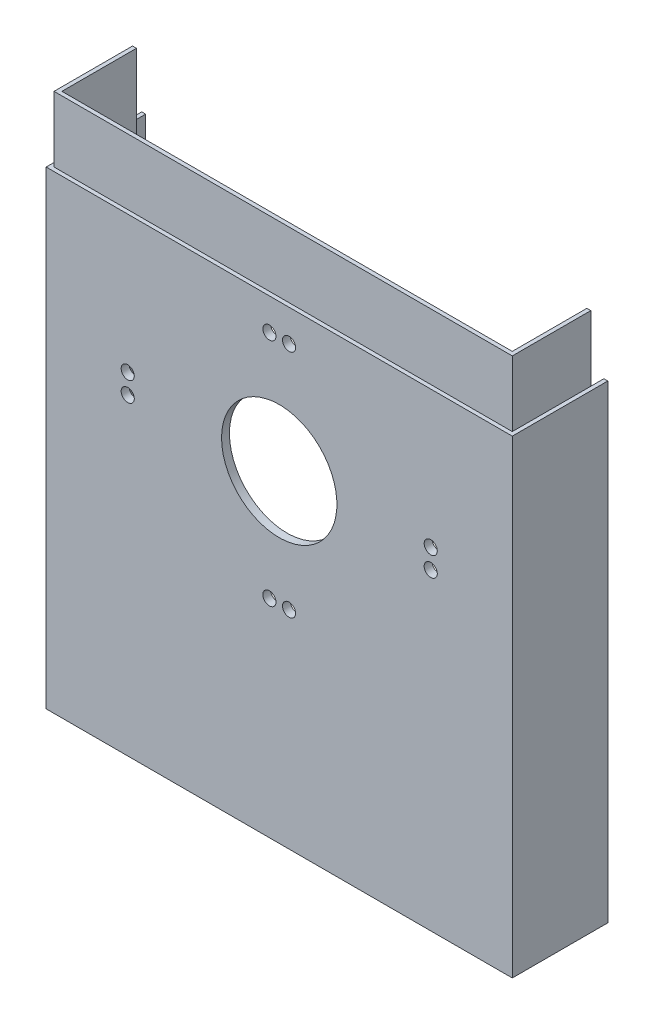
SolidWorks part; units mm, degrees
ref_plane "Front Plane" through (0, 0, 0) normal (0, 0, 1) x (1, 0, 0)
ref_plane "Top Plane" through (0, 0, 0) normal (0, 1, 0) x (1, 0, 0)
ref_plane "Right Plane" through (0, 0, 0) normal (1, 0, 0) x (0, 0, -1)
sketch "Sketch1" plane through (0, 0, 0) normal (0, 0, 1) x (1, 0, 0)
  line L1 (-88.9, -127) -> (88.9, -127)
  line L2 (-88.9, -127) -> (-88.9, 127)
  line L3 (-88.9, 127) -> (88.9, 127)
  line L4 (88.9, -127) -> (88.9, 127)
  line L5 (-88.9, -127) -> (88.9, 127) construction
  line L6 (-88.9, 127) -> (88.9, -127) construction
  point P0 (0, 0)
  dimension "D1" = 177.8
  dimension "D2" = 254
extrude "Boss-Extrude1" add sketch "Sketch1" along normal mid plane 72.89
shell "Shell1" thickness 3
sketch "Sketch2" plane through (0, 0, 33.445) normal (0, 0, -1) x (-1, 0, 0)
  line L0 (85.9, -124) -> (-85.9, -124) construction
  line L1 (-3.75, -47.9079) -> (3.75, -47.9079) construction
  line L2 (-57.789, -0.25) -> (-57.789, -7.75) construction
  line L3 (-1000, -4) -> (49000, -4) construction
  line L4 (0, -1004) -> (0, 48996) construction
  circle A0 centre (0, -4) radius 22
  circle A1 centre (-3.75, -47.9079) radius 2.5
  circle A2 centre (3.75, -47.9079) radius 2.5
  circle A3 centre (-57.789, -0.25) radius 2.5
  circle A4 centre (-57.789, -7.75) radius 2.5
  circle A5 centre (57.789, -0.25) radius 2.5
  circle A6 centre (57.789, -7.75) radius 2.5
  circle A7 centre (3.75, 39.9079) radius 2.5
  circle A8 centre (-3.75, 39.9079) radius 2.5
  ellipse E0 centre (0, -4) end of major axis (58, -4) minor radius 44 construction
  point P12 (0, -47.9079)
  point P19 (-57.789, -4)
  dimension "D1" = 44
  dimension "D3" = 88
  dimension "D4" = 116
  dimension "D5" = 5
  dimension "D2" = 120
  dimension "D6" = 7.5
  dimension "D7" = 7.5
extrude "Cut-Extrude1" cut sketch "Sketch2" against normal blind 3
sketch "Sketch3" plane through (0, 0, -33.445) normal (0, 0, 1) x (1, 0, 0)
  line L0 (85.9, 124) -> (-85.9, 124) construction
  line L1 (-85.9, 124) -> (-85.9, -124) construction
  circle A0 centre (-20.9, 34) radius 5
  dimension "D3" = 10
  dimension "D1" = 90
  dimension "D2" = 65
extrude "Cut-Extrude2" cut sketch "Sketch3" against normal blind 3
sketch "Sketch12" plane through (0, 124, 0) normal (0, -1, 0) x (1, 0, 0)
  line L0 (85.9, -33.445) -> (-85.9, -33.445) construction
  line L1 (6, 33.445) -> (-6, 33.445)
  line L2 (6, 33.445) -> (6, -33.445)
  line L3 (6, -33.445) -> (-6, -33.445)
  line L4 (-6, 33.445) -> (-6, -33.445)
  line L5 (6, 33.445) -> (-6, -33.445) construction
  line L6 (6, -33.445) -> (-6, 33.445) construction
  point P0 (0, 0)
  dimension "D1" = 12
extrude "Boss-Extrude5" add sketch "Sketch12" along normal blind 8
sketch "Sketch10" plane through (0, 127, 0) normal (0, 1, 0) x (1, 0, 0)
  circle A0 centre (0, 0) radius 3
  dimension "D1" = 6
extrude "Cut-Extrude8" cut sketch "Sketch10" against normal blind 8 contours A0
ref_plane "Plane2" through (0, 52, 0) normal (0, 1, 0) x (1, 0, 0)
split "Split2" trim tools "Plane2" bodies to split 123 resulting bodies 126 127
sketch "Sketch13" plane through (0, 52, 0) normal (0, 1, 0) x (1, 0, 0)
  line L4 (-85.9, 33.445) -> (-85.9, -33.445)
  line L5 (-85.9, -33.445) -> (85.9, -33.445)
  line L6 (85.9, -33.445) -> (85.9, 33.445)
  line L7 (85.9, 33.445) -> (-85.9, 33.445)
  line L8 (-87.4, 34.945) -> (-87.4, -34.945)
  line L9 (-87.4, -34.945) -> (87.4, -34.945)
  line L10 (87.4, -34.945) -> (87.4, 34.945)
  line L11 (87.4, 34.945) -> (-87.4, 34.945)
  line L12 (-87.4, 34.945) -> (-87.4, -34.945)
  line L13 (-87.4, -34.945) -> (87.4, -34.945)
  line L14 (87.4, -34.945) -> (87.4, 34.945)
  line L15 (87.4, 34.945) -> (-87.4, 34.945)
  dimension "D1" = 1.5
  dimension "D2" = 1.5
extrude "Boss-Extrude6" add sketch "Sketch13" along normal blind 25
sketch "Sketch14" plane through (0, 52, 0) normal (0, -1, 0) x (1, 0, 0)
  line L7 (-85.9, 33.445) -> (-85.9, -33.445)
  line L8 (-85.9, -33.445) -> (85.9, -33.445)
  line L9 (85.9, -33.445) -> (85.9, 33.445)
  line L10 (85.9, 33.445) -> (-85.9, 33.445)
  line L11 (-87.65, 35.195) -> (-87.65, -35.195)
  line L12 (-87.65, -35.195) -> (87.65, -35.195)
  line L13 (87.65, -35.195) -> (87.65, 35.195)
  line L14 (87.65, 35.195) -> (-87.65, 35.195)
  line L15 (-87.65, 35.195) -> (-87.65, -35.195)
  line L16 (-87.65, -35.195) -> (87.65, -35.195)
  line L17 (87.65, -35.195) -> (87.65, 35.195)
  line L18 (87.65, 35.195) -> (-87.65, 35.195)
  dimension "D1" = 1.75
  dimension "D2" = 1.75
extrude "Cut-Extrude9" cut sketch "Sketch14" against normal blind 10
sketch "Sketch17" plane through (0, -124, 0) normal (0, 1, 0) x (1, 0, 0)
  line L1 (-85.9, 33.445) -> (85.9, 33.445)
  line L2 (-85.9, 33.445) -> (-85.9, -33.445)
  line L3 (-85.9, -33.445) -> (85.9, -33.445)
  line L4 (85.9, 33.445) -> (85.9, -33.445)
  line L5 (-85.9, 33.445) -> (85.9, -33.445) construction
  line L6 (-85.9, -33.445) -> (85.9, 33.445) construction
  point P4 (0, 0)
extrude "Boss-Extrude7" add sketch "Sketch17" along normal blind 2
sketch "Sketch22" plane through (0, -127, 0) normal (0, -1, 0) x (1, 0, 0)
  line L0 (-921.6829, 0) -> (49078.3171, 0) construction
  line L1 (11.6047, 0) -> (5.8024, 10.05)
  line L2 (5.8024, 10.05) -> (-5.8024, 10.05)
  line L3 (-5.8024, 10.05) -> (-11.6047, 0)
  line L4 (-11.6047, 0) -> (-5.8024, -10.05)
  line L5 (-5.8024, -10.05) -> (5.8024, -10.05)
  line L6 (5.8024, -10.05) -> (11.6047, 0)
  line L7 (-20.1777, 15.1777) -> (-15.1777, 15.1777)
  line L8 (-20.1777, 15.1777) -> (-20.1777, 20.1777)
  line L9 (-20.1777, 20.1777) -> (-15.1777, 20.1777)
  line L10 (-15.1777, 15.1777) -> (-15.1777, 20.1777)
  line L11 (-20.1777, 15.1777) -> (-15.1777, 20.1777) construction
  line L12 (-20.1777, 20.1777) -> (-15.1777, 15.1777) construction
  line L13 (0, 0) -> (-17.6777, 17.6777) construction
  line L14 (15.1777, 20.1777) -> (20.1777, 20.1777)
  line L15 (15.1777, 20.1777) -> (15.1777, 15.1777)
  line L16 (15.1777, 15.1777) -> (20.1777, 15.1777)
  line L17 (20.1777, 20.1777) -> (20.1777, 15.1777)
  line L18 (20.1777, -15.1777) -> (20.1777, -20.1777)
  line L19 (20.1777, -15.1777) -> (15.1777, -15.1777)
  line L20 (15.1777, -15.1777) -> (15.1777, -20.1777)
  line L21 (20.1777, -20.1777) -> (15.1777, -20.1777)
  line L22 (-15.1777, -20.1777) -> (-20.1777, -20.1777)
  line L23 (-15.1777, -20.1777) -> (-15.1777, -15.1777)
  line L24 (-15.1777, -15.1777) -> (-20.1777, -15.1777)
  line L25 (-20.1777, -20.1777) -> (-20.1777, -15.1777)
  line L26 (0, 0) -> (-15.1777, 15.1777) construction
  line L27 (0, 0) -> (15.1777, 15.1777) construction
  circle A1 centre (0, 0) radius 10.05 construction
  circle A2 centre (0, 0) radius 25 construction
  point P3 (-17.6777, 17.6777)
  dimension "D1" = 50
  dimension "D2" = 20.1
  dimension "D3" = 5
  dimension "D4" = 45
  dimension "D6" = 90
  dimension "D5" = 4
extrude "Cut-Extrude14" cut sketch "Sketch22" against normal blind 5
split "Split3" trim tools "Front Plane" bodies to split 140 132 resulting bodies 133 134
sketch "Sketch19" plane through (0, 0, 0) normal (0, 0, 1) x (1, 0, 0)
  line L0 (87.4, 52) -> (87.4, 77) construction
  line L1 (-87.4, 77) -> (-85.9, 77)
  line L2 (-87.4, 77) -> (-87.4, -123.5)
  line L3 (-87.4, -123.5) -> (-11.6047, -123.5)
  line L4 (87.4, 77) -> (87.4, -123.5)
  line L5 (-87.4, 77) -> (87.4, -123.5) construction
  line L6 (-87.4, -123.5) -> (87.4, 77) construction
  line L7 (11.6047, -122) -> (11.6047, -127) construction
  line L8 (-85.9, -122) -> (-11.6047, -122) construction
  line L9 (85.9, 77) -> (-85.9, 77) construction
  line L10 (-87.4, 77) -> (-87.4, 52) construction
  line L11 (-85.9, 75.5) -> (-85.9, -122)
  line L12 (-85.9, -122) -> (-11.6047, -122)
  line L13 (85.9, 75.5) -> (85.9, -122)
  line L15 (-11.6047, -122) -> (-11.6047, -123.5)
  line L17 (11.6047, -122) -> (11.6047, -123.5)
  line L19 (11.6047, -122) -> (85.9, -122)
  line L20 (-85.9, -122) -> (85.9, -122) construction
  line L21 (11.6047, -123.5) -> (87.4, -123.5)
  line L22 (-87.4, -123.5) -> (87.4, -123.5) construction
  line L23 (-85.9, 75.5) -> (-85.9, 77)
  line L24 (85.9, 75.5) -> (85.9, 77)
  line L25 (85.9, 77) -> (87.4, 77)
  line L26 (-87.4, 77) -> (87.4, 77) construction
  line L27 (-85.9, 75.5) -> (85.9, 75.5) construction
  line L28 (-11.6047, -122) -> (-11.6047, -127) construction
  line L29 (-5.8024, -122) -> (-11.6047, -122) construction
  point P4 (0, -23.25)
  dimension "D1" = 1.5
extrude "Boss-Extrude8" add sketch "Sketch19" along normal blind 5
sketch "Sketch20" plane through (0, 0, 0) normal (0, 0, -1) x (-1, 0, 0)
  line L0 (-87.4, 77) -> (-87.4, -123.5)
  line L2 (-85.9, 77) -> (-85.9, -122)
  line L3 (-85.9, -122) -> (-11.6047, -122)
  line L4 (85.9, 77) -> (85.9, -122)
  line L5 (-85.9, 77) -> (85.9, -122) construction
  line L6 (-85.9, -122) -> (85.9, 77) construction
  line L7 (-87.4, -123.5) -> (-11.6047, -123.5)
  line L8 (87.4, 77) -> (87.4, -123.5)
  line L10 (-87.4, 77) -> (-85.9, 77)
  line L11 (85.9, 77) -> (87.4, 77)
  line L12 (-85.9, -122) -> (-85.9, 77) construction
  line L13 (85.9, 77) -> (85.9, -122) construction
  line L14 (-11.6047, -123.5) -> (-11.6047, -122)
  line L15 (11.6047, -123.5) -> (11.6047, -122)
  line L16 (11.6047, -122) -> (85.9, -122)
  line L17 (11.6047, -123.5) -> (87.4, -123.5)
  point P4 (0, -22.5)
extrude "Cut-Extrude12" cut sketch "Sketch20" against normal blind 5
sketch "Sketch21" plane through (0, 0, 0) normal (0, 0, -1) x (-1, 0, 0)
  line L1 (-11.6047, -122) -> (11.6047, -122)
  line L2 (-11.6047, -122) -> (-11.6047, -123.5)
  line L3 (-11.6047, -123.5) -> (11.6047, -123.5)
  line L4 (11.6047, -122) -> (11.6047, -123.5)
  line L5 (-11.6047, -122) -> (11.6047, -123.5) construction
  line L6 (-11.6047, -123.5) -> (11.6047, -122) construction
  line L8 (-11.6047, -122) -> (-11.6047, -123.5) construction
  line L9 (5.8024, -122) -> (11.6047, -122) construction
  line L10 (11.6047, -122) -> (11.6047, -123.5) construction
  line L12 (11.6047, -123.5) -> (87.4, -123.5) construction
  point P4 (0, -122.75)
extrude "Cut-Extrude13" cut sketch "Sketch21" against normal up to surface (5 mm away) up to face at (65.3156, -40.7143, 5)
delete or keep bodies "Body-Delete/Keep 1" type delete bodies bodies 129
delete or keep bodies "Body-Delete/Keep 2" type delete bodies bodies 135
